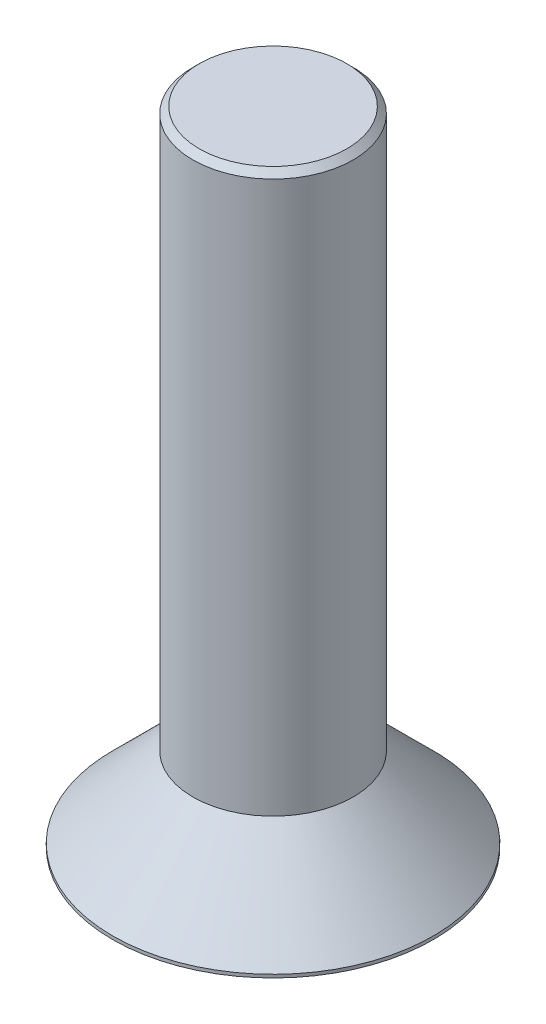
SolidWorks part; units mm, degrees
ref_plane "前视基准面" through (0, 0, 0) normal (0, 0, 1) x (1, 0, 0)
ref_plane "上视基准面" through (0, 0, 0) normal (0, 1, 0) x (1, 0, 0)
ref_plane "右视基准面" through (0, 0, 0) normal (1, 0, 0) x (0, 0, -1)
sketch "草图1" plane through (0, 0, 0) normal (0, 1, 0) x (1, 0, 0)
  circle A0 centre (0, 0) radius 5
  dimension "D1" = 10
extrude "凸台-拉伸1" add sketch "草图1" along normal blind 2.6
chamfer "倒角1" distance 2.5 angle 45 1 edges at (0, 2.6, 5)
sketch "草图2" plane through (0, 0, 0) normal (0, -1, 0) x (1, 0, 0)
  line L1 (1.54, -0.8891) -> (1.54, 0.8891)
  line L2 (1.54, 0.8891) -> (0, 1.7782)
  line L3 (0, 1.7782) -> (-1.54, 0.8891)
  line L4 (-1.54, 0.8891) -> (-1.54, -0.8891)
  line L5 (-1.54, -0.8891) -> (0, -1.7782)
  line L6 (0, -1.7782) -> (1.54, -0.8891)
  circle A0 centre (0, 0) radius 1.54 construction
  dimension "D1" = 3.08
extrude "切除-拉伸1" cut sketch "草图2" against normal blind 0.95
sketch "草图3" plane through (0, 2.6, 0) normal (0, 1, 0) x (1, 0, 0)
  circle A0 centre (0, 0) radius 2.5
  dimension "D1" = 5
extrude "凸台-拉伸2" add sketch "草图3" along normal blind 17.4
chamfer "倒角2" distance 0.2 angle 45 1 edges at (0, 20, 2.5)
